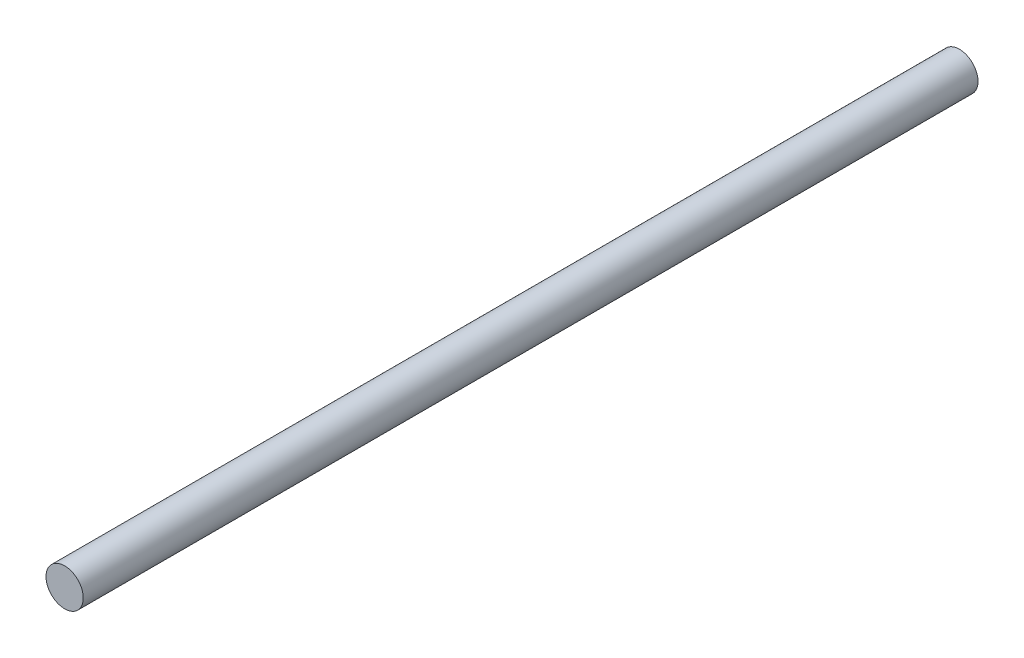
SolidWorks part; units mm, degrees
ref_plane "Front" through (0, 0, 0) normal (0, 0, 1) x (1, 0, 0)
ref_plane "Top" through (0, 0, 0) normal (0, 1, 0) x (1, 0, 0)
ref_plane "Right" through (0, 0, 0) normal (1, 0, 0) x (0, 0, -1)
sketch "Sketch1" plane through (0, 0, 0) normal (0, 0, 1) x (1, 0, 0)
  circle A0 centre (0, 0) radius 1.5875
  point P3 (0, 0)
extrude "Boss-Extrude1" add sketch "Sketch1" along normal blind 76.2
